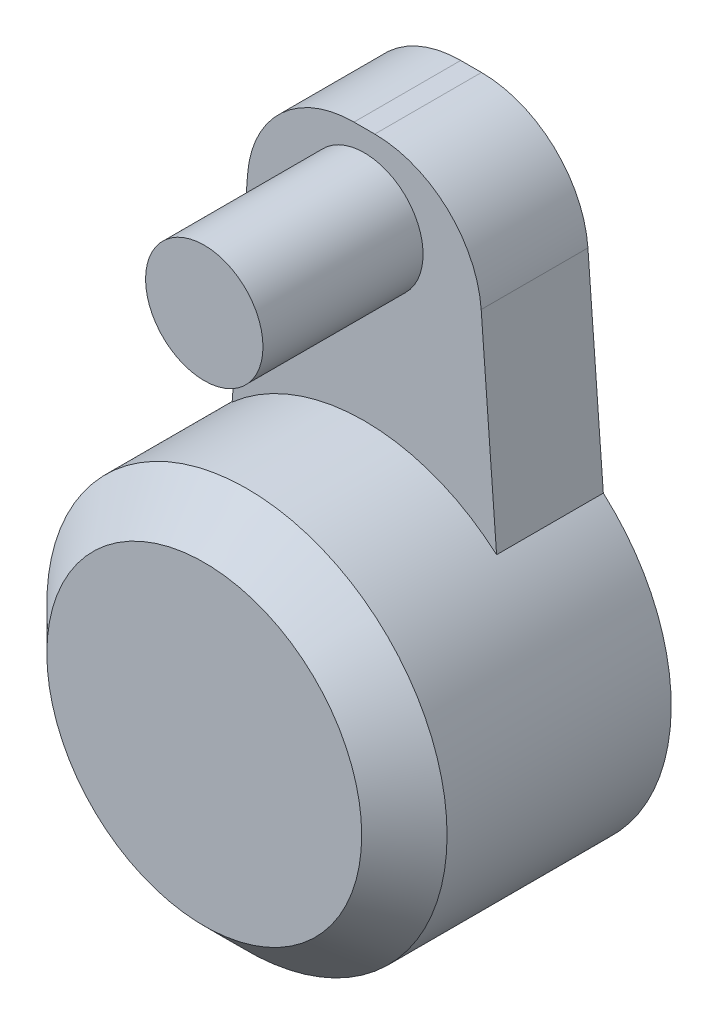
SolidWorks part; units mm, degrees
ref_plane "前视基准面" through (0, 0, 0) normal (0, 0, 1) x (1, 0, 0)
ref_plane "上视基准面" through (0, 0, 0) normal (0, 1, 0) x (1, 0, 0)
ref_plane "右视基准面" through (0, 0, 0) normal (1, 0, 0) x (0, 0, -1)
other "Configuration Table"
sketch "草图1" plane through (0, 0, 0) normal (0, 0, 1) x (1, 0, 0)
  line L0 (-2.1891, -0.35) -> (-2.65, -6.4775)
  line L1 (-2.65, -6.4775) -> (2.65, -6.4775)
  line L2 (2.65, -6.4775) -> (2.1891, -0.35)
  line L3 (-0.1948, 1.5) -> (0.1948, 1.5)
  line L4 (0, 0.5515) -> (0, 2.5678) construction
  arc A1 (0.1948, 1.5) -> (2.1891, -0.35) centre (0.1948, -0.5) cw
  arc A2 (-0.1948, 1.5) -> (-2.1891, -0.35) centre (-0.1948, -0.5) ccw
  point P11 (2.05, 1.5)
  point P14 (-2.05, 1.5)
  dimension "D1" = 1.5
  dimension "D5" = 2
  dimension "D2" = 8
  dimension "D3" = 5.3
  dimension "D4" = 4.1
extrude "凸台-拉伸1" add sketch "草图1" along normal blind 2
sketch "草图2" plane through (0, 0, 2) normal (0, 0, 1) x (1, 0, 0)
  circle A0 centre (0, 0) radius 1.1
  dimension "D1" = 2.2
extrude "凸台-拉伸2" add sketch "草图2" along normal blind 3
sketch "草图3" plane through (0, 0, 0) normal (0, 0, 1) x (1, 0, 0)
  line L0 (0, -1000) -> (0, 49000) construction
  circle A0 centre (0, -7) radius 3.75
  dimension "D2" = 7.5
  dimension "D1" = 7
extrude "凸台-拉伸3" add sketch "草图3" along normal blind 5
chamfer "倒角1" distance 0.8 angle 45 1 edges at (3.75, -7, 5)
sketch "草图4" plane through (0, 0, 0) normal (0, 0, -1) x (-1, 0, 0)
  circle A0 centre (0, -7) radius 1.1
  dimension "D1" = 2.2
extrude "切除-拉伸1" cut sketch "草图4" against normal blind 4
sketch "草图5" plane through (0, 0, 0) normal (0, 0, -1) x (-1, 0, 0)
  circle A0 centre (0, -7) radius 2.25
  dimension "D1" = 4.5
extrude "切除-拉伸2" cut sketch "草图5" against normal blind 1.5
